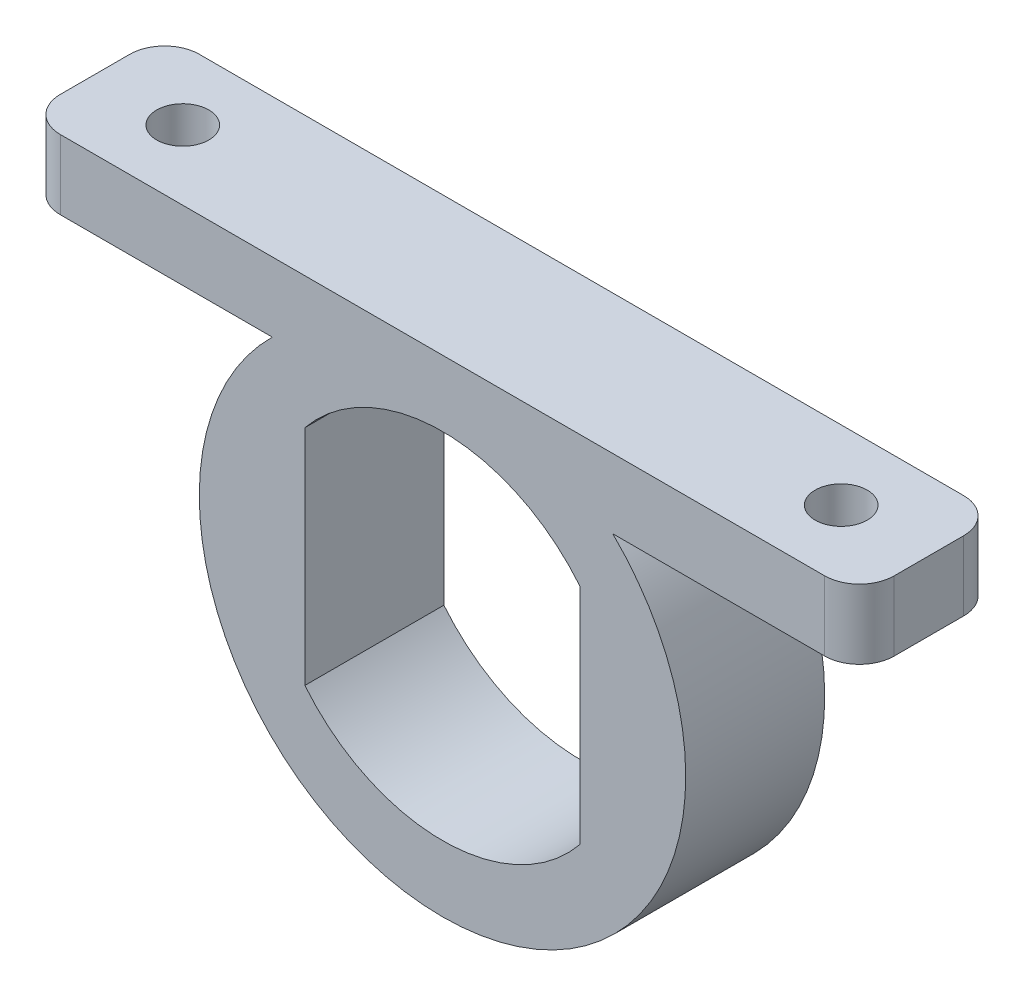
SolidWorks part; units mm, degrees
ref_plane "Alzado" through (0, 0, 0) normal (0, 0, 1) x (1, 0, 0)
ref_plane "Planta" through (0, 0, 0) normal (0, 1, 0) x (1, 0, 0)
ref_plane "Vista lateral" through (0, 0, 0) normal (1, 0, 0) x (0, 0, -1)
sketch "Croquis1" plane through (0, 0, 0) normal (0, 0, 1) x (1, 0, 0)
  line L0 (0, 14) -> (-24, 14)
  line L1 (-24, 14) -> (-24, 10)
  line L2 (-24, 10) -> (-9.798, 10)
  line L3 (0, 14) -> (24, 14)
  line L4 (24, 14) -> (24, 10)
  line L5 (0, -10) -> (0, 10) construction
  line L6 (24, 10) -> (9.798, 10)
  circle A0 centre (0, 0) radius 10
  arc A1 (-9.798, 10) -> (9.798, 10) centre (0, 0) ccw
  dimension "D1" = 20
  dimension "D2" = 48
  dimension "D5" = 24
  dimension "D4" = 4
  dimension "D3" = 14
extrude "Saliente-Extruir1" add sketch "Croquis1" along normal blind 8 contours L4 L6 A1 L2 L1 L0 L3
sketch "Croquis2" plane through (0, 0, 8) normal (0, 0, 1) x (1, 0, 0)
  line L0 (-7.9221, 6.425) -> (-7.9221, -6.425)
  line L1 (7.9221, 6.425) -> (7.9221, -6.425)
  arc A0 (-7.9221, 6.425) -> (7.9221, 6.425) centre (0, 0) cw
  arc A1 (-7.9221, -6.425) -> (7.9221, -6.425) centre (0, 0) ccw
  dimension "D1" = 15.8442
  dimension "D2" = 10.2
  dimension "D4" = 10.2
  dimension "D3" = 7.9221
extrude "Cortar-Extruir1" cut sketch "Croquis2" against normal through all
fillet "Redondeo1" radius 2 4 edges at (24, 12, 0) (24, 12, 8) (-24, 12, 0) (-24, 12, 8)
sketch "Croquis3" plane through (0, 10, 0) normal (0, -1, 0) x (-1, 0, 0)
  line L0 (22, -8) -> (15.899, 0) construction
  line L1 (22, 0) -> (9.798, 0) construction
  line L2 (-22, -8) -> (-15.899, 0) construction
  line L3 (-22, 0) -> (-9.798, 0) construction
  circle A0 centre (18.9495, -4) radius 1.5
  circle A1 centre (-18.9495, -4) radius 1.5
  dimension "D1" = 3
  dimension "D2" = 3
extrude "Cortar-Extruir2" cut sketch "Croquis3" against normal through all
